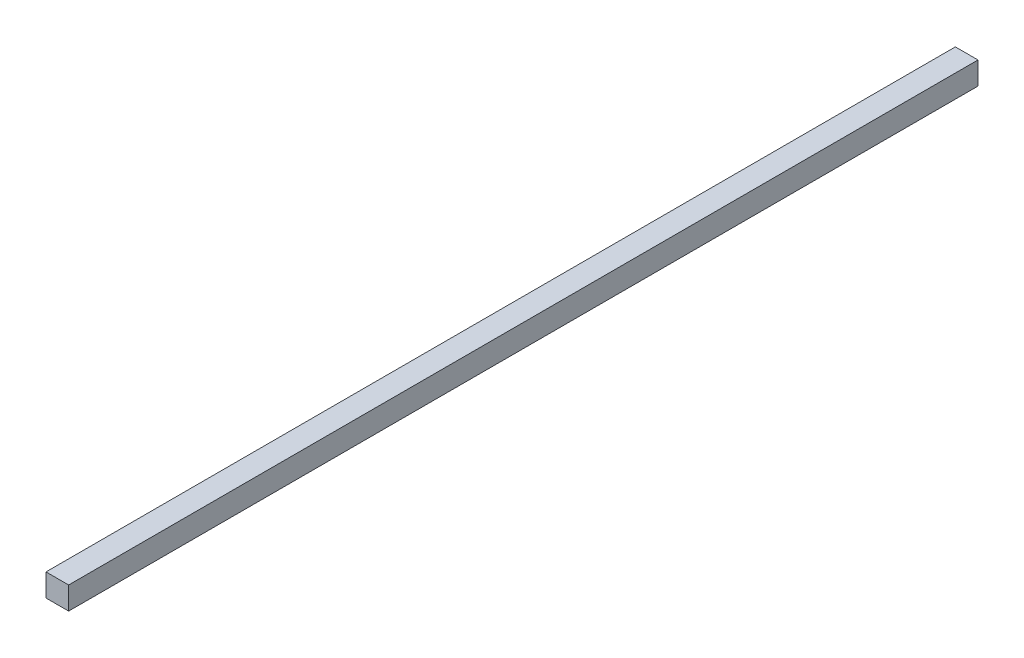
SolidWorks part; units mm, degrees
material "AISI Type A2 Tool Steel"
ref_plane "Front Plane" through (0, 0, 0) normal (0, 0, 1) x (1, 0, 0)
ref_plane "Top Plane" through (0, 0, 0) normal (0, 1, 0) x (1, 0, 0)
ref_plane "Right Plane" through (0, 0, 0) normal (1, 0, 0) x (0, 0, -1)
sketch "Sketch1" plane through (0, 0, 0) normal (0, 0, 1) x (1, 0, 0)
  line L0 (-3.175, 0) -> (3.175, 0) construction
  line L1 (0, -3.175) -> (0, 3.175) construction
  line L5 (-3.175, 3.175) -> (3.175, 3.175) construction
  line L7 (-3.175, 3.175) -> (-3.175, -3.175) construction
  line L8 (3.175, -3.175) -> (3.175, 3.175) construction
  line L13 (-3.175, -3.175) -> (3.175, -3.175) construction
  point P0 (0, 0)
  point P4 (0, 0)
  point P9 (0, 0)
  point P22 (0, 3.175)
  dimension "Thickness" = 6.35
  dimension "D1" = 6.35
sketch "Sketch2" plane through (0, 0, 0) normal (0, 1, 0) x (0, 0, -1)
  line L0 (127.5, 0) -> (-127.5, 0) construction
  line L2 (-127.5, 3.175) -> (127.5, 3.175) construction
  line L3 (-127.5, 3.175) -> (-127.5, -3.175) construction
  line L4 (-127.5, -3.175) -> (127.5, -3.175) construction
  line L5 (127.5, 3.175) -> (127.5, -3.175) construction
  line L6 (-127.5, 3.175) -> (127.5, -3.175) construction
  line L7 (-127.5, -3.175) -> (127.5, 3.175) construction
  point P4 (0, 0)
  point P7 (0, 0)
  point P12 (-117.975, 3.175)
  point P13 (117.975, 3.175)
  dimension "Length" = 255
  dimension "Width" = 6.35
  dimension "D1" = 9.525
  dimension "D2" = 9.525
sketch "Sketch3" plane through (0, 0, 0) normal (0, 0, 1) x (1, 0, 0)
  line L3 (-3.175, 3.175) -> (3.175, 3.175)
  line L17 (3.175, 3.175) -> (3.175, -3.175)
  line L18 (3.175, -3.175) -> (-3.175, -3.175)
  line L19 (-3.175, -3.175) -> (-3.175, 3.175)
extrude "Boss-Extrude1" add sketch "Sketch3" along normal mid plane 255
equation "\"D1@Boss-Extrude1\" = \"Length@Sketch2\""
equation "\"D1@Sketch1\"=\"Width@Sketch2\""
equation "\"D1@Sketch2\"=\"Width@Sketch2\"*1.5"
equation "\"D2@Sketch2\"=\"D1@Sketch2\""
